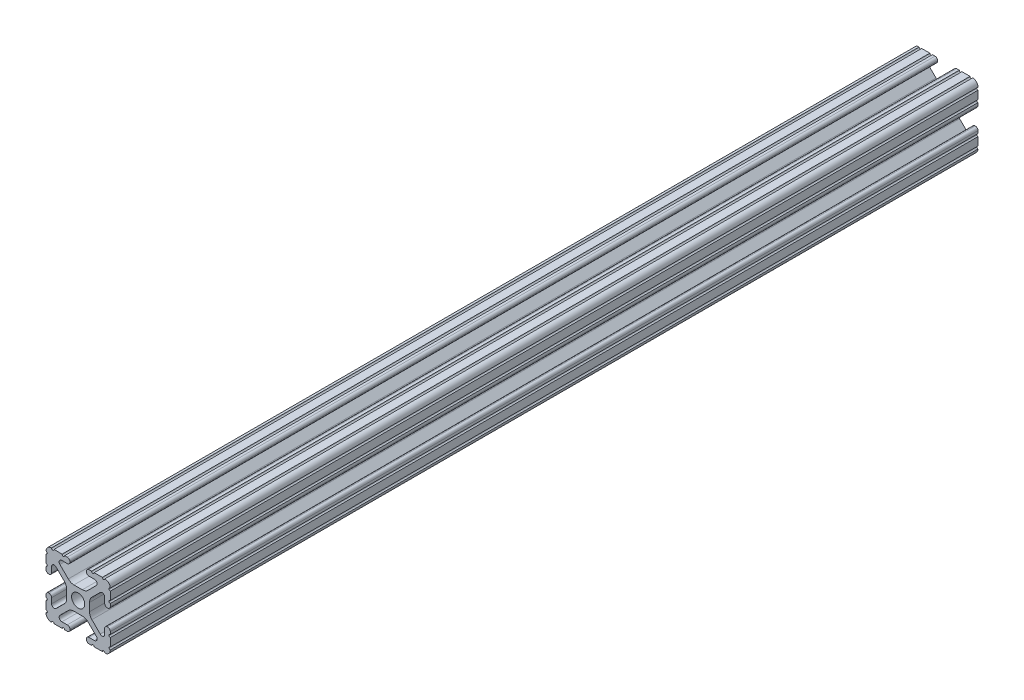
SolidWorks part; units mm, degrees
ref_plane "Front Plane" through (0, 0, 0) normal (0, 0, 1) x (1, 0, 0)
ref_plane "Top Plane" through (0, 0, 0) normal (0, 1, 0) x (1, 0, 0)
ref_plane "Right Plane" through (0, 0, 0) normal (1, 0, 0) x (0, 0, -1)
sketch "Sketch1" plane through (0, 0, 0) normal (0, 0, 1) x (1, 0, 0)
  line L88 (-7.1797, -8.6452) -> (-3.9523, -5.4237)
  line L89 (-1.7093, -4.4958) -> (1.7093, -4.4958)
  line L90 (3.9523, -5.4237) -> (7.1797, -8.6452)
  line L91 (6.4164, -10.4902) -> (4.2875, -10.4902)
  line L92 (3.2385, -11.5392) -> (3.2385, -11.651)
  line L93 (4.2875, -12.7) -> (5.3171, -12.7)
  line L94 (6.3331, -12.7) -> (9.5504, -12.7)
  line L95 (12.7, -9.5504) -> (12.7, -6.3331)
  line L96 (12.7, -5.3171) -> (12.7, -4.2875)
  line L97 (11.651, -3.2385) -> (11.5392, -3.2385)
  line L98 (10.4902, -4.2875) -> (10.4902, -6.4021)
  line L99 (8.7371, -7.1294) -> (5.441, -3.8408)
  line L100 (4.5085, -1.5932) -> (4.5085, 1.5932)
  line L101 (5.441, 3.8408) -> (8.7371, 7.1294)
  line L102 (10.4902, 6.4021) -> (10.4902, 4.2875)
  line L103 (11.5392, 3.2385) -> (11.651, 3.2385)
  line L104 (12.7, 4.2875) -> (12.7, 5.3171)
  line L105 (12.7, 6.3331) -> (12.7, 9.5504)
  line L106 (9.5504, 12.7) -> (6.3331, 12.7)
  line L107 (5.3171, 12.7) -> (4.2875, 12.7)
  line L108 (3.2385, 11.651) -> (3.2385, 11.5392)
  line L109 (4.2875, 10.4902) -> (6.4768, 10.4902)
  line L110 (7.207, 8.7244) -> (3.8983, 5.4232)
  line L111 (1.6558, 4.4958) -> (-1.6558, 4.4958)
  line L112 (-3.8983, 5.4232) -> (-7.207, 8.7244)
  line L113 (-6.4768, 10.4902) -> (-4.2875, 10.4902)
  line L114 (-3.2385, 11.5392) -> (-3.2385, 11.651)
  line L115 (-4.2875, 12.7) -> (-5.3171, 12.7)
  line L116 (-6.3331, 12.7) -> (-9.5504, 12.7)
  line L117 (-12.7, 9.5504) -> (-12.7, 6.3331)
  line L118 (-12.7, 5.3171) -> (-12.7, 4.2875)
  line L119 (-11.651, 3.2385) -> (-11.5392, 3.2385)
  line L120 (-10.4902, 4.2875) -> (-10.4902, 6.4021)
  line L121 (-8.7371, 7.1294) -> (-5.441, 3.8408)
  line L122 (-4.5085, 1.5932) -> (-4.5085, -1.5932)
  line L123 (-5.441, -3.8408) -> (-8.7371, -7.1294)
  line L124 (-10.4902, -6.4021) -> (-10.4902, -4.2875)
  line L125 (-11.5392, -3.2385) -> (-11.651, -3.2385)
  line L126 (-12.7, -4.2875) -> (-12.7, -5.3171)
  line L127 (-12.7, -6.3331) -> (-12.7, -9.5504)
  line L128 (-9.5504, -12.7) -> (-6.3331, -12.7)
  line L129 (-5.3171, -12.7) -> (-4.2875, -12.7)
  line L130 (-3.2385, -11.651) -> (-3.2385, -11.5392)
  line L131 (-4.2875, -10.4902) -> (-6.4164, -10.4902)
  circle A1 centre (0, 0) radius 2.6035
  arc A104 (-7.1797, -8.6452) -> (-6.4164, -10.4902) centre (-6.4164, -9.4098) ccw
  arc A105 (-1.7093, -4.4958) -> (-3.9523, -5.4237) centre (-1.7093, -7.6708) ccw
  arc A106 (3.9523, -5.4237) -> (1.7093, -4.4958) centre (1.7093, -7.6708) ccw
  arc A107 (6.4164, -10.4902) -> (7.1797, -8.6452) centre (6.4164, -9.4098) ccw
  arc A108 (4.2875, -10.4902) -> (3.2385, -11.5392) centre (4.2875, -11.5392) ccw
  arc A109 (3.2385, -11.651) -> (4.2875, -12.7) centre (4.2875, -11.651) ccw
  arc A110 (6.3331, -12.7) -> (5.3171, -12.7) centre (5.8251, -12.7) ccw
  arc A111 (10.5664, -12.6998) -> (9.5504, -12.7) centre (10.0584, -12.7) ccw
  arc A112 (10.5664, -12.6998) -> (12.6998, -10.5664) centre (10.5918, -10.5918) ccw
  arc A113 (12.7, -9.5504) -> (12.6998, -10.5664) centre (12.7, -10.0584) ccw
  arc A114 (12.7, -5.3171) -> (12.7, -6.3331) centre (12.7, -5.8251) ccw
  arc A115 (12.7, -4.2875) -> (11.651, -3.2385) centre (11.651, -4.2875) ccw
  arc A116 (11.5392, -3.2385) -> (10.4902, -4.2875) centre (11.5392, -4.2875) ccw
  arc A117 (8.7371, -7.1294) -> (10.4902, -6.4021) centre (9.4628, -6.4021) ccw
  arc A118 (4.5085, -1.5932) -> (5.441, -3.8408) centre (7.6835, -1.5932) ccw
  arc A119 (5.441, 3.8408) -> (4.5085, 1.5932) centre (7.6835, 1.5932) ccw
  arc A120 (10.4902, 6.4021) -> (8.7371, 7.1294) centre (9.4628, 6.4021) ccw
  arc A121 (10.4902, 4.2875) -> (11.5392, 3.2385) centre (11.5392, 4.2875) ccw
  arc A122 (11.651, 3.2385) -> (12.7, 4.2875) centre (11.651, 4.2875) ccw
  arc A123 (12.7, 6.3331) -> (12.7, 5.3171) centre (12.7, 5.8251) ccw
  arc A124 (12.6998, 10.5664) -> (12.7, 9.5504) centre (12.7, 10.0584) ccw
  arc A125 (12.6998, 10.5664) -> (10.5664, 12.6998) centre (10.5918, 10.5918) ccw
  arc A126 (9.5504, 12.7) -> (10.5664, 12.6998) centre (10.0584, 12.7) ccw
  arc A127 (5.3171, 12.7) -> (6.3331, 12.7) centre (5.8251, 12.7) ccw
  arc A128 (4.2875, 12.7) -> (3.2385, 11.651) centre (4.2875, 11.651) ccw
  arc A129 (3.2385, 11.5392) -> (4.2875, 10.4902) centre (4.2875, 11.5392) ccw
  arc A130 (7.207, 8.7244) -> (6.4768, 10.4902) centre (6.4768, 9.4563) ccw
  arc A131 (1.6558, 4.4958) -> (3.8983, 5.4232) centre (1.6558, 7.6708) ccw
  arc A132 (-3.8983, 5.4232) -> (-1.6558, 4.4958) centre (-1.6558, 7.6708) ccw
  arc A133 (-6.4768, 10.4902) -> (-7.207, 8.7244) centre (-6.4768, 9.4563) ccw
  arc A134 (-4.2875, 10.4902) -> (-3.2385, 11.5392) centre (-4.2875, 11.5392) ccw
  arc A135 (-3.2385, 11.651) -> (-4.2875, 12.7) centre (-4.2875, 11.651) ccw
  arc A136 (-6.3331, 12.7) -> (-5.3171, 12.7) centre (-5.8251, 12.7) ccw
  arc A137 (-10.5664, 12.6998) -> (-9.5504, 12.7) centre (-10.0584, 12.7) ccw
  arc A138 (-10.5664, 12.6998) -> (-12.6998, 10.5664) centre (-10.5918, 10.5918) ccw
  arc A139 (-12.7, 9.5504) -> (-12.6998, 10.5664) centre (-12.7, 10.0584) ccw
  arc A140 (-12.7, 5.3171) -> (-12.7, 6.3331) centre (-12.7, 5.8251) ccw
  arc A141 (-12.7, 4.2875) -> (-11.651, 3.2385) centre (-11.651, 4.2875) ccw
  arc A142 (-11.5392, 3.2385) -> (-10.4902, 4.2875) centre (-11.5392, 4.2875) ccw
  arc A143 (-8.7371, 7.1294) -> (-10.4902, 6.4021) centre (-9.4628, 6.4021) ccw
  arc A144 (-4.5085, 1.5932) -> (-5.441, 3.8408) centre (-7.6835, 1.5932) ccw
  arc A145 (-5.441, -3.8408) -> (-4.5085, -1.5932) centre (-7.6835, -1.5932) ccw
  arc A146 (-10.4902, -6.4021) -> (-8.7371, -7.1294) centre (-9.4628, -6.4021) ccw
  arc A147 (-10.4902, -4.2875) -> (-11.5392, -3.2385) centre (-11.5392, -4.2875) ccw
  arc A148 (-11.651, -3.2385) -> (-12.7, -4.2875) centre (-11.651, -4.2875) ccw
  arc A149 (-12.7, -6.3331) -> (-12.7, -5.3171) centre (-12.7, -5.8251) ccw
  arc A150 (-12.6998, -10.5664) -> (-12.7, -9.5504) centre (-12.7, -10.0584) ccw
  arc A151 (-12.6998, -10.5664) -> (-10.5664, -12.6998) centre (-10.5918, -10.5918) ccw
  arc A152 (-9.5504, -12.7) -> (-10.5664, -12.6998) centre (-10.0584, -12.7) ccw
  arc A153 (-5.3171, -12.7) -> (-6.3331, -12.7) centre (-5.8251, -12.7) ccw
  arc A154 (-4.2875, -12.7) -> (-3.2385, -11.651) centre (-4.2875, -11.651) ccw
  arc A155 (-3.2385, -11.5392) -> (-4.2875, -10.4902) centre (-4.2875, -11.5392) ccw
extrude "Boss-Extrude1" add sketch "Sketch1" along normal mid plane 342.9
